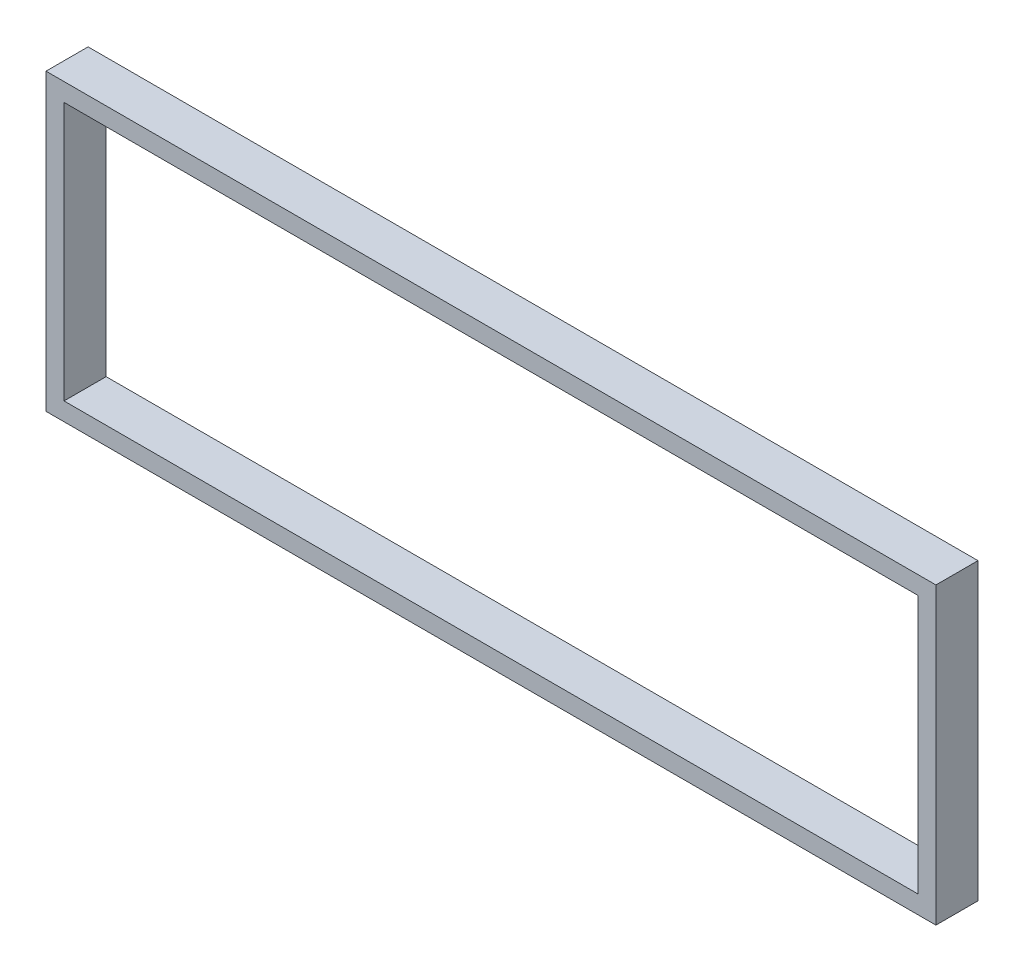
SolidWorks part; units mm, degrees
ref_plane "Front Plane" through (0, 0, 0) normal (0, 0, 1) x (1, 0, 0)
ref_plane "Top Plane" through (0, 0, 0) normal (0, 1, 0) x (1, 0, 0)
ref_plane "Right Plane" through (0, 0, 0) normal (1, 0, 0) x (0, 0, -1)
sketch "Sketch1" plane through (0, 0, 0) normal (0, 0, 1) x (1, 0, 0)
  line L1 (0, 0) -> (148, 0)
  line L2 (0, 0) -> (0, 49)
  line L3 (0, 49) -> (148, 49)
  line L4 (148, 0) -> (148, 49)
  line L5 (3, 3) -> (145, 3)
  line L6 (3, 3) -> (3, 46)
  line L7 (3, 46) -> (145, 46)
  line L8 (145, 3) -> (145, 46)
  dimension "D1" = 3
  dimension "D2" = 145
  dimension "D3" = 148
  dimension "D4" = 3
  dimension "D5" = 46
  dimension "D6" = 49
extrude "Profile" add sketch "Sketch1" along normal blind 7
equation "\"Profile_Depth\" = 7mm"
equation "\"D1@Profile\" = \"Profile_Depth\""
equation "\"Profile_Sketch_1\" = 3mm"
equation "\"D1@Sketch1\" = \"Profile_Sketch_1\""
equation "\"Profile_Sketch_2\" = 145mm"
equation "\"D2@Sketch1\" = \"Profile_Sketch_2\""
equation "\"Profile_Sketch_3\" = 148mm"
equation "\"D3@Sketch1\" = \"Profile_Sketch_3\""
equation "\"Profile_Sketch_4\" = 3mm"
equation "\"D4@Sketch1\" = \"Profile_Sketch_4\""
equation "\"Profile_Sketch_5\" = 46mm"
equation "\"D5@Sketch1\" = \"Profile_Sketch_5\""
equation "\"Profile_Sketch_6\" = 49mm"
equation "\"D6@Sketch1\" = \"Profile_Sketch_6\""
equation "\"EnvelopeWidth\" = 148mm"
equation "\"EnvelopeHeight\" = 49mm"
